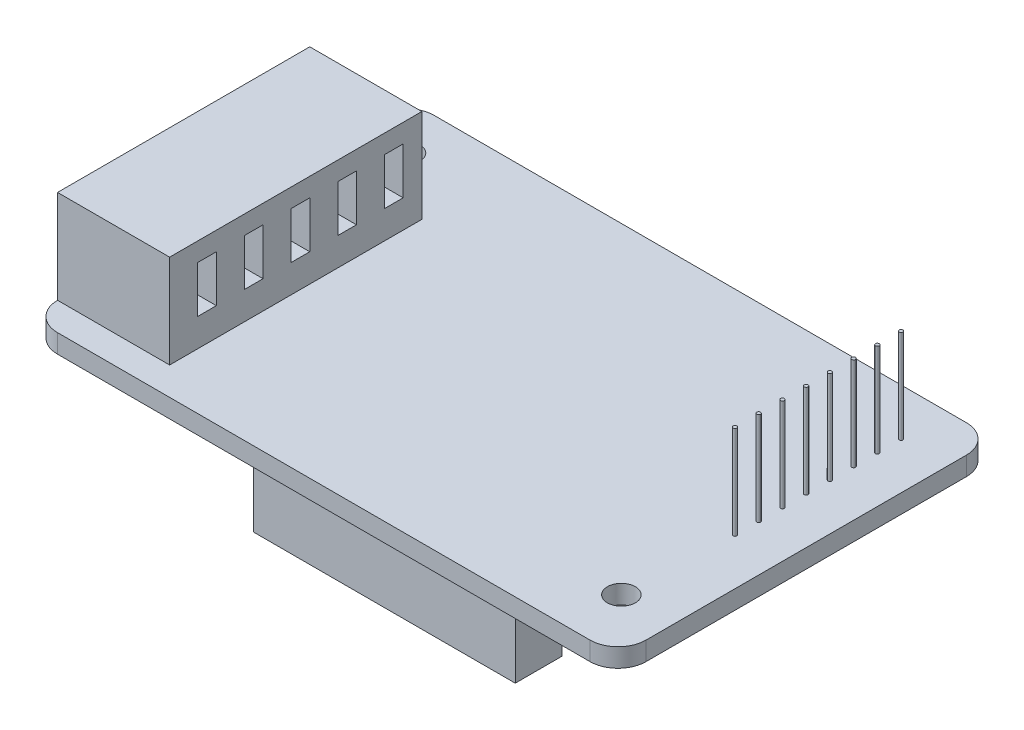
SolidWorks part; units mm, degrees
ref_plane "前视基准面" through (0, 0, 0) normal (0, 0, 1) x (1, 0, 0)
ref_plane "上视基准面" through (0, 0, 0) normal (0, 1, 0) x (1, 0, 0)
ref_plane "右视基准面" through (0, 0, 0) normal (1, 0, 0) x (0, 0, -1)
sketch "草图1" plane through (0, 0, 0) normal (0, 1, 0) x (1, 0, 0)
  line L1 (-31.5, -20.15) -> (31.5, -20.15)
  line L2 (-31.5, -20.15) -> (-31.5, 20.15)
  line L3 (-31.5, 20.15) -> (31.5, 20.15)
  line L4 (31.5, -20.15) -> (31.5, 20.15)
  line L5 (-31.5, -20.15) -> (31.5, 20.15) construction
  line L6 (-31.5, 20.15) -> (31.5, -20.15) construction
  point P0 (0, 0)
  dimension "D1" = 40.3
  dimension "D2" = 63
extrude "凸台-拉伸1" add sketch "草图1" along normal blind 2
sketch "草图2" plane through (0, 2, 0) normal (0, 1, 0) x (1, 0, 0)
  line L0 (-31.5, 20.15) -> (-31.5, -20.15) construction
  line L1 (31.5, 20.15) -> (-31.5, 20.15) construction
  circle A0 centre (-26.5, 15.15) radius 1.5
  circle A1 centre (25.98, -14.27) radius 1.5
  dimension "D1" = 3
  dimension "D2" = 5
  dimension "D3" = 5
  dimension "D4" = 3
  dimension "D5" = 29.42
  dimension "D6" = 52.48
extrude "切除-拉伸1" cut sketch "草图2" against normal up to next
fillet "圆角1" radius 3 4 edges at (31.5, 1, -20.15) (31.5, 1, 20.15) (-31.5, 1, 20.15) (-31.5, 1, -20.15)
sketch "草图3" plane through (0, 0, 0) normal (0, -1, 0) x (-1, 0, 0)
  line L0 (-28.5, 20.15) -> (28.5, 20.15) construction
  line L1 (20.5, 16.15) -> (-20.5, 16.15)
  line L2 (20.5, 16.15) -> (20.5, 11.15)
  line L3 (20.5, 11.15) -> (-20.5, 11.15)
  line L4 (-20.5, 16.15) -> (-20.5, 11.15)
  line L5 (11.5, -11.15) -> (-16.5, -11.15)
  line L6 (11.5, -11.15) -> (11.5, -16.15)
  line L7 (11.5, -16.15) -> (-16.5, -16.15)
  line L8 (-16.5, -11.15) -> (-16.5, -16.15)
  line L9 (31.5, 17.15) -> (31.5, -17.15) construction
  line L10 (-31.5, -17.15) -> (-31.5, 17.15) construction
  line L11 (28.5, -20.15) -> (-28.5, -20.15) construction
  dimension "D1" = 5
  dimension "D2" = 4
  dimension "D3" = 11
  dimension "D4" = 11
  dimension "D5" = 20
  dimension "D6" = 15
  dimension "D7" = 5
  dimension "D8" = 4
extrude "凸台-拉伸2" add sketch "草图3" along normal blind 10
sketch "草图4" plane through (0, 2, 0) normal (0, 1, 0) x (1, 0, 0)
  line L0 (-31.5, 17.15) -> (-31.5, -17.15) construction
  line L1 (-19.5, 9.85) -> (-31.5, 9.85)
  line L2 (-19.5, 9.85) -> (-19.5, -17.15)
  line L3 (-19.5, -17.15) -> (-31.5, -17.15)
  line L4 (-31.5, 9.85) -> (-31.5, -17.15)
  line L5 (-28.5, -20.15) -> (28.5, -20.15) construction
  dimension "D1" = 27
  dimension "D2" = 3
  dimension "D3" = 12
extrude "凸台-拉伸3" add sketch "草图4" along normal blind 10
sketch "草图5" plane through (-31.5, 0, 0) normal (-1, 0, 0) x (0, 0, 1)
  line L0 (-9.85, 12) -> (17.15, 12) construction
  line L1 (-7.85, 10) -> (-5.85, 10)
  line L2 (-7.85, 10) -> (-7.85, 5)
  line L3 (-7.85, 5) -> (-5.85, 5)
  line L4 (-5.85, 10) -> (-5.85, 5)
  line L5 (-9.85, 12) -> (-9.85, 2) construction
  dimension "D1" = 2
  dimension "D2" = 2
  dimension "D3" = 2
extrude "切除-拉伸2" cut sketch "草图5" against normal up to next
pattern_linear "阵列(线性)1" count 5 spacing 5 along (0, 0, 1) of "切除-拉伸2"
sketch "草图6" plane through (0, 2, 0) normal (0, 1, 0) x (1, 0, 0)
  line L0 (28.5, 20.15) -> (-28.5, 20.15) construction
  line L1 (31.5, -17.15) -> (31.5, 17.15) construction
  circle A0 centre (26.5, 15.15) radius 0.2
  dimension "D1" = 0.4
  dimension "D2" = 5
  dimension "D3" = 5
extrude "凸台-拉伸4" add sketch "草图6" along normal blind 10
pattern_linear "阵列(线性)2" count 8 spacing 2.54 along (0, 0, 1) of "凸台-拉伸4"
